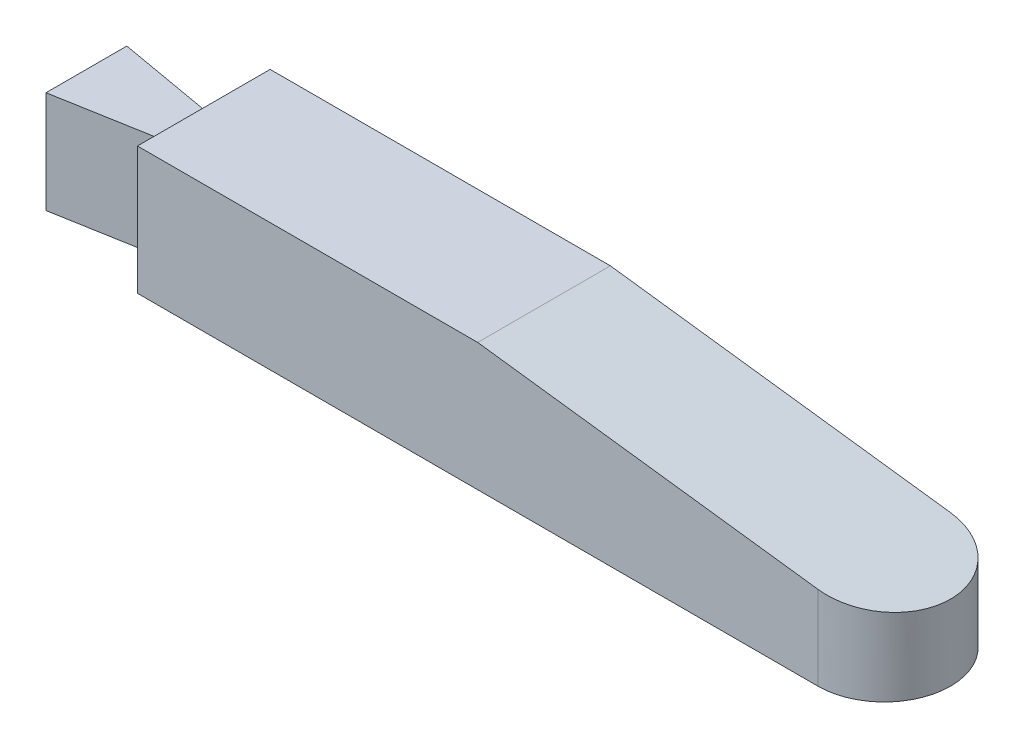
SolidWorks part; units mm, degrees
ref_plane "Front Plane" through (0, 0, 0) normal (0, 0, 1) x (1, 0, 0)
ref_plane "Top Plane" through (0, 0, 0) normal (0, 1, 0) x (1, 0, 0)
ref_plane "Right Plane" through (0, 0, 0) normal (1, 0, 0) x (0, 0, -1)
sketch "Sketch2" plane through (0, 0, 0) normal (0, 1, 0) x (1, 0, 0)
  line L10 (21.5028, -14.8255) -> (21.5028, -26.5943) construction
  line L29 (-13.5492, -8.6449) -> (-13.5492, -32.7749)
  line L30 (-13.5492, -8.6449) -> (21.5028, -14.8255)
  line L31 (-13.5492, -32.7749) -> (21.5028, -26.5943)
  line L32 (21.5028, -0.8979) -> (224.7028, -0.8979)
  line L33 (21.5028, -40.5219) -> (224.7028, -40.5219)
  line L35 (21.5028, -0.8979) -> (21.5028, -14.8255)
  line L36 (21.5028, -40.5219) -> (21.5028, -26.5943)
  line L37 (-13.5492, -20.7099) -> (21.5028, -20.7099) construction
  arc A5 (224.7028, -0.8979) -> (224.7028, -40.5219) centre (224.7028, -20.7099) cw
  dimension "D4" = 80
  dimension "D5" = 39.624
  dimension "D3" = 80
  dimension "D2" = 24.13
  dimension "D6" = 203.2
  dimension "D9" = 13.5492
  dimension "D10" = 26.1183
  dimension "D11" = 13.9276
  dimension "D14" = 35.052
extrude "Boss-Extrude1" add sketch "Sketch2" along normal blind 38.1
sketch "Sketch3" plane through (0, 38.1, 0) normal (0, 1, 0) x (1, 0, 0)
  line L0 (-13.5492, -8.6449) -> (-13.5492, -32.7749)
  line L1 (-13.5492, -32.7749) -> (21.5028, -26.5943)
  line L2 (21.5028, -26.5943) -> (21.5028, -14.8255)
  line L3 (21.5028, -14.8255) -> (-13.5492, -8.6449)
extrude "Cut-Extrude1" cut sketch "Sketch3" against normal blind 7.62
sketch "Sketch5" plane through (0, 0, 40.5219) normal (0, 0, 1) x (1, 0, 0)
  line L5 (123.1028, 38.1) -> (244.5148, 22.5197)
  line L6 (21.5028, 38.1) -> (224.7028, 38.1) construction
  line L7 (244.5148, 0) -> (244.5148, 38.1) construction
  line L8 (244.5148, 22.5197) -> (244.5148, 38.1)
  line L9 (244.5148, 38.1) -> (123.1028, 38.1)
  dimension "D1" = 7.313
extrude "Cut-Extrude4" cut sketch "Sketch5" against normal blind 39.624
